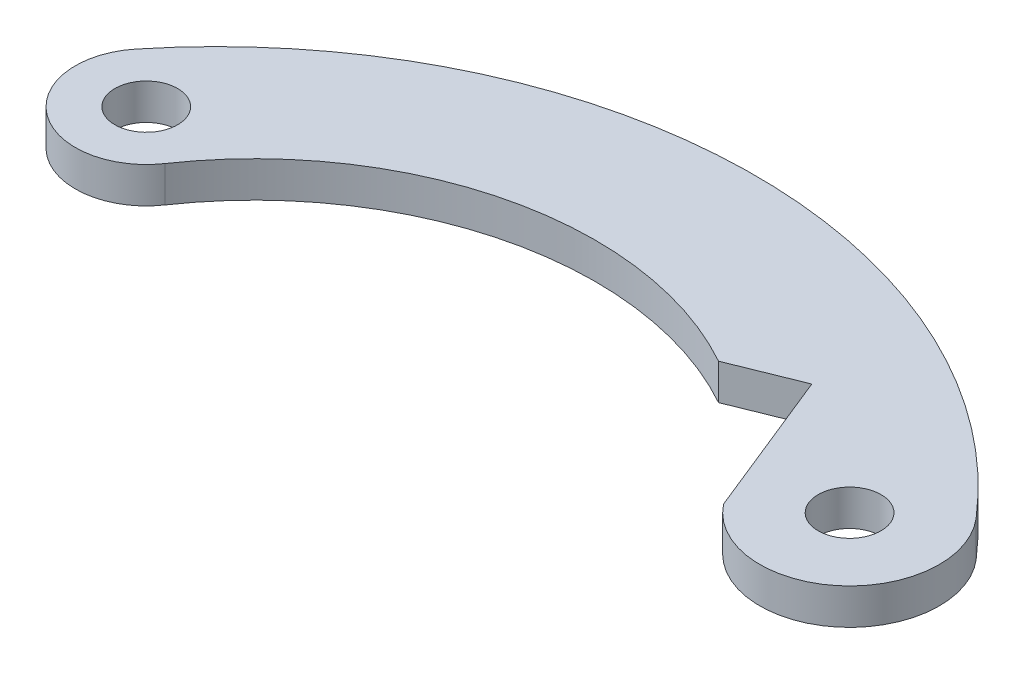
SolidWorks part; units mm, degrees
ref_plane "Front Plane" through (0, 0, 0) normal (0, 0, 1) x (1, 0, 0)
ref_plane "Top Plane" through (0, 0, 0) normal (0, 1, 0) x (1, 0, 0)
ref_plane "Right Plane" through (0, 0, 0) normal (1, 0, 0) x (0, 0, -1)
sketch "Sketch1" plane through (0, 0, 0) normal (0, 1, 0) x (1, 0, 0)
  line L0 (0, 25.5178) -> (0, -32.2544) construction
  line L1 (0, 0) -> (39.1784, 0) construction
  arc A0 (-3.0741, 2.4804) -> (3.2633, -2.2256) centre (0, 0) ccw
  arc A1 (34.9663, -2.694) -> (42.9594, 3.2717) centre (39.1784, 0) ccw
  arc A2 (3.2633, -2.2256) -> (34.9663, -2.694) centre (18.9601, -12.9313) cw
  arc A3 (-3.0741, 2.4804) -> (42.9594, 3.2717) centre (20.2733, -16.3584) cw
  circle A4 centre (0, 0) radius 1.75
  circle A5 centre (39.1784, 0) radius 1.75
  dimension "D2" = 7.9
  dimension "D3" = 10
  dimension "D4" = 30
  dimension "D5" = 19
  dimension "D6" = 3.5
  dimension "D7" = 3.5
  dimension "D1" = 39.1784
extrude "Boss-Extrude1" add sketch "Sketch1" along normal mid plane 2
sketch "Sketch2" plane through (0, 0, 0) normal (0, 1, 0) x (1, 0, 0)
  line L0 (39.1784, 0) -> (1.9553, -15.0391) construction
  line L1 (0, 0) -> (39.1784, 0) construction
  line L2 (36.1765, -5.3834) -> (31.9184, 5.1558)
  line L3 (31.9184, 5.1558) -> (14.2308, -1.9905)
  line L4 (14.2308, -1.9905) -> (18.4889, -12.5296)
  line L5 (18.4889, -12.5296) -> (36.1765, -5.3834)
  dimension "D1" = 4.8
  dimension "D2" = 7.5
  dimension "D3" = 22
extrude "Cut-Extrude1" cut sketch "Sketch2" against normal through all both and the other way through all
